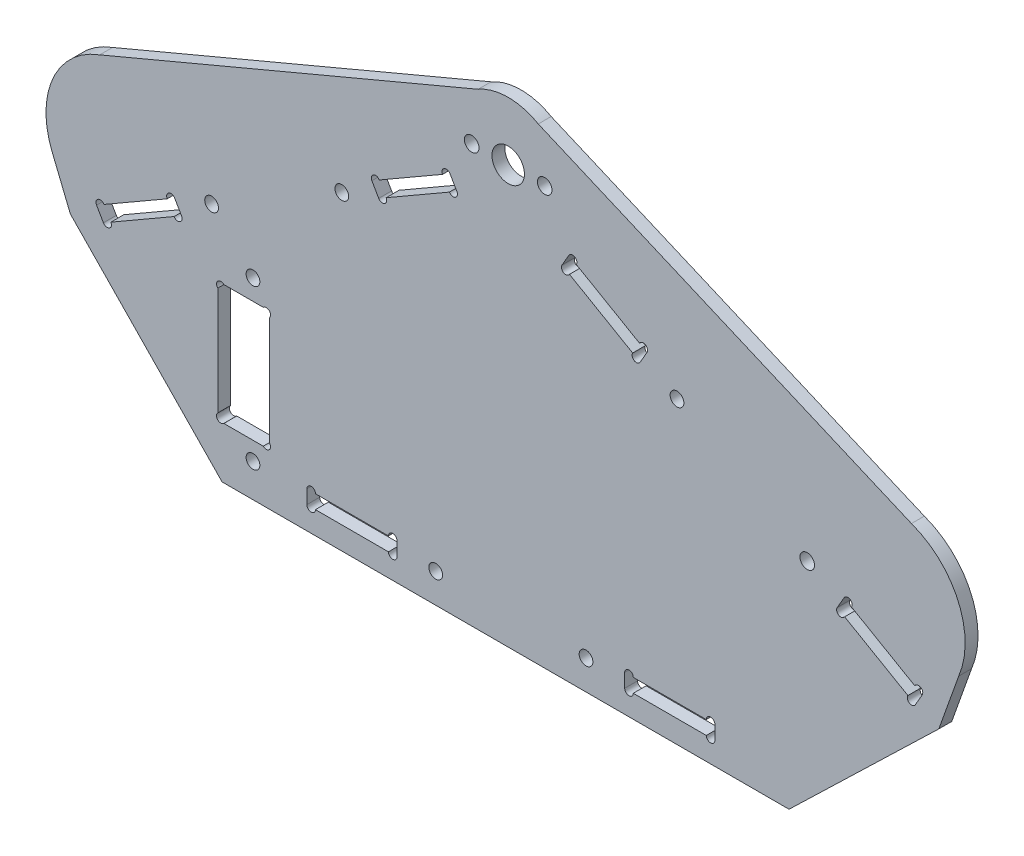
SolidWorks part; units mm, degrees
ref_plane "Front Plane" through (0, 0, 0) normal (0, 0, 1) x (1, 0, 0)
ref_plane "Top Plane" through (0, 0, 0) normal (0, 1, 0) x (1, 0, 0)
ref_plane "Right Plane" through (0, 0, 0) normal (1, 0, 0) x (0, 0, -1)
sketch "Model" plane through (0, 0, 0) normal (0, 0, 1) x (1, 0, 0)
  line L0 (99, 100) -> (99, 72)
  line L1 (99, 72) -> (87, 72)
  line L2 (87, 72) -> (87, 100)
  line L3 (87, 100) -> (99, 100)
  line L4 (88, 60) -> (220, 60)
  line L5 (88, 60) -> (52.6771, 96.363)
  line L6 (52.6771, 96.363) -> (48.5104, 106.5761)
  line L7 (220, 60) -> (254.8826, 93.6405)
  line L8 (254.8826, 93.6405) -> (259.4896, 106.5761)
  line L9 (147.6171, 168.9801) -> (59.5016, 131.8542)
  line L10 (161.6171, 168.9801) -> (248.4984, 131.8542)
  line L11 (181.7345, 65.2574) -> (181.7355, 68.4574)
  line L12 (249.3993, 95.7703) -> (231.2162, 106.2761)
  line L13 (60.3746, 98.4289) -> (58.7755, 101.2007)
  line L14 (251.0002, 98.5411) -> (232.8171, 109.0469)
  line L15 (181.7355, 68.4574) -> (202.7355, 68.4507)
  line L16 (128.7345, 65.2744) -> (128.7355, 68.4744)
  line L18 (78.5645, 108.9231) -> (76.9654, 111.6949)
  line L19 (142.6622, 145.9026) -> (124.4723, 135.4084)
  line L20 (107.7355, 68.4811) -> (128.7355, 68.4744)
  line L21 (136.0359, 145.7741) -> (122.8732, 138.1802)
  line L22 (251.0002, 98.5411) -> (249.3993, 95.7703)
  line L23 (58.7755, 101.2007) -> (76.9654, 111.6949)
  line L24 (141.0631, 148.6744) -> (142.6622, 145.9026)
  line L25 (141.0631, 148.6744) -> (136.0359, 145.7741)
  line L26 (181.7345, 65.2574) -> (202.7345, 65.2507)
  line L28 (167.1422, 143.2967) -> (168.7431, 146.0675)
  line L29 (232.8171, 109.0469) -> (231.2162, 106.2761)
  line L31 (122.8732, 138.1802) -> (124.4723, 135.4084)
  line L32 (185.3253, 132.7909) -> (186.9262, 135.5616)
  line L33 (202.7345, 65.2507) -> (202.7355, 68.4507)
  line L35 (107.7345, 65.2811) -> (107.7355, 68.4811)
  line L36 (168.7431, 146.0675) -> (186.9262, 135.5616)
  line L37 (60.3746, 98.4289) -> (78.5645, 108.9231)
  line L38 (167.1422, 143.2967) -> (185.3253, 132.7909)
  line L39 (107.7345, 65.2811) -> (128.7345, 65.2744)
  arc A2 (59.5016, 131.8542) -> (48.5104, 106.5761) centre (66, 114) ccw
  arc A3 (161.6171, 168.9801) -> (147.6171, 168.9801) centre (154.6171, 156.8557) ccw
  arc A4 (259.4896, 106.5761) -> (248.4984, 131.8542) centre (242, 114) ccw
  circle A5 centre (154.6171, 157.238) radius 3.7816
  circle A6 centre (163.1146, 157.238) radius 1.7
  circle A7 centre (146.1171, 157.238) radius 1.7
  circle A8 centre (115.8771, 132.2968) radius 1.6
  circle A10 centre (137.735, 66.8715) radius 1.6
  circle A11 centre (193.9186, 129.6737) radius 1.6
  circle A13 centre (172.735, 66.8715) radius 1.6
  circle A19 centre (95.2, 104.75) radius 1.6
  circle A20 centre (85.5606, 114.8065) radius 1.6
  circle A21 centre (224.2337, 112.1583) radius 1.7
  circle A22 centre (95.2, 67.75) radius 1.6
  dimension "D7" = 3.2
  dimension "D8" = 3.2
  dimension "D9" = 1.6
  dimension "D10" = 3.2
  dimension "D11" = 1.6
  dimension "D12" = 1.6
  dimension "D13" = 3.2
  dimension "D14" = 1.6
  dimension "D15" = 1.6
  dimension "D16" = 53
extrude "Boss-Extrude2" add sketch "Model" along normal blind 3
sketch "Sketch1" plane through (0, 0, 3) normal (0, 0, 1) x (1, 0, 0)
  line L0 (60.3746, 98.4289) -> (78.5645, 108.9231) construction
  line L1 (76.9654, 111.6949) -> (58.7755, 101.2007) construction
  line L2 (128.7355, 68.4744) -> (107.7355, 68.4811) construction
  line L3 (107.7345, 65.2811) -> (128.7345, 65.2744) construction
  line L4 (181.7345, 65.2574) -> (202.7345, 65.2507) construction
  line L5 (202.7355, 68.4507) -> (181.7355, 68.4574) construction
  line L6 (231.2162, 106.2761) -> (249.3993, 95.7703) construction
  line L7 (251.0002, 98.5411) -> (232.8171, 109.0469) construction
  line L8 (167.1422, 143.2967) -> (185.3253, 132.7909) construction
  line L9 (186.9262, 135.5616) -> (168.7431, 146.0675) construction
  line L10 (124.4723, 135.4084) -> (142.6622, 145.9026) construction
  line L11 (141.0631, 148.6744) -> (136.0359, 145.7741) construction
  line L12 (136.0359, 145.7741) -> (122.8732, 138.1802) construction
  line L13 (87, 100) -> (87.7075, 99.2925) construction
  line L14 (99, 100) -> (98.2925, 99.2925) construction
  line L15 (87, 72) -> (87.7075, 72.7075) construction
  line L16 (99, 72) -> (98.2925, 72.7075) construction
  line L22 (99, 100) -> (87, 100) construction
  circle A0 centre (61.2412, 98.9289) radius 1.0005
  circle A1 centre (59.6421, 101.7007) radius 1.0005
  circle A2 centre (76.0988, 111.1949) radius 1.0005
  circle A3 centre (77.6979, 108.4232) radius 1.0005
  circle A4 centre (87.7075, 99.2925) radius 1.0005
  circle A5 centre (98.2925, 99.2925) radius 1.0005
  circle A6 centre (87.7075, 72.7075) radius 1.0005
  circle A7 centre (98.2925, 72.7075) radius 1.0005
  circle A8 centre (108.736, 68.4808) radius 1.0005
  circle A9 centre (108.735, 65.2808) radius 1.0005
  circle A10 centre (127.734, 65.2747) radius 1.0005
  circle A11 centre (127.735, 68.4747) radius 1.0005
  circle A12 centre (182.735, 65.2571) radius 1.0005
  circle A13 centre (182.736, 68.4571) radius 1.0005
  circle A14 centre (201.735, 68.451) radius 1.0005
  circle A15 centre (201.734, 65.251) radius 1.0005
  circle A16 centre (232.0825, 105.7756) radius 1.0005
  circle A17 centre (233.6834, 108.5464) radius 1.0005
  circle A18 centre (250.1339, 99.0416) radius 1.0005
  circle A19 centre (248.5331, 96.2708) radius 1.0005
  circle A24 centre (168.0085, 142.7962) radius 1.0005
  circle A25 centre (169.6094, 145.5669) radius 1.0005
  circle A26 centre (184.459, 133.2914) radius 1.0005
  circle A27 centre (186.0599, 136.0622) radius 1.0005
  circle A28 centre (141.7956, 145.4026) radius 1.0005
  circle A29 centre (140.1965, 148.1744) radius 1.0005
  circle A30 centre (123.7399, 138.6802) radius 1.0005
  circle A31 centre (125.339, 135.9084) radius 1.0005
  dimension "D2" = 2.001
  dimension "D3" = 45
extrude "Cut-Extrude1" cut sketch "Sketch1" against normal through all
sketch "Sketch2" plane through (0, 0, 3) normal (0, 0, 1) x (1, 0, 0)
  line L0 (47, 99.0563) -> (47, 142.0642) construction
  line L1 (114.5947, 170.8557) -> (196.8499, 170.8557) construction
  arc A1 (59.5016, 131.8542) -> (48.5104, 106.5761) centre (66, 114) ccw construction
  arc A2 (161.6171, 168.9801) -> (147.6171, 168.9801) centre (154.6171, 156.8557) ccw construction
equation "\"dim-top\"= 2.001"
equation "\"D2@Sketch1\"=\"dim-top\""
